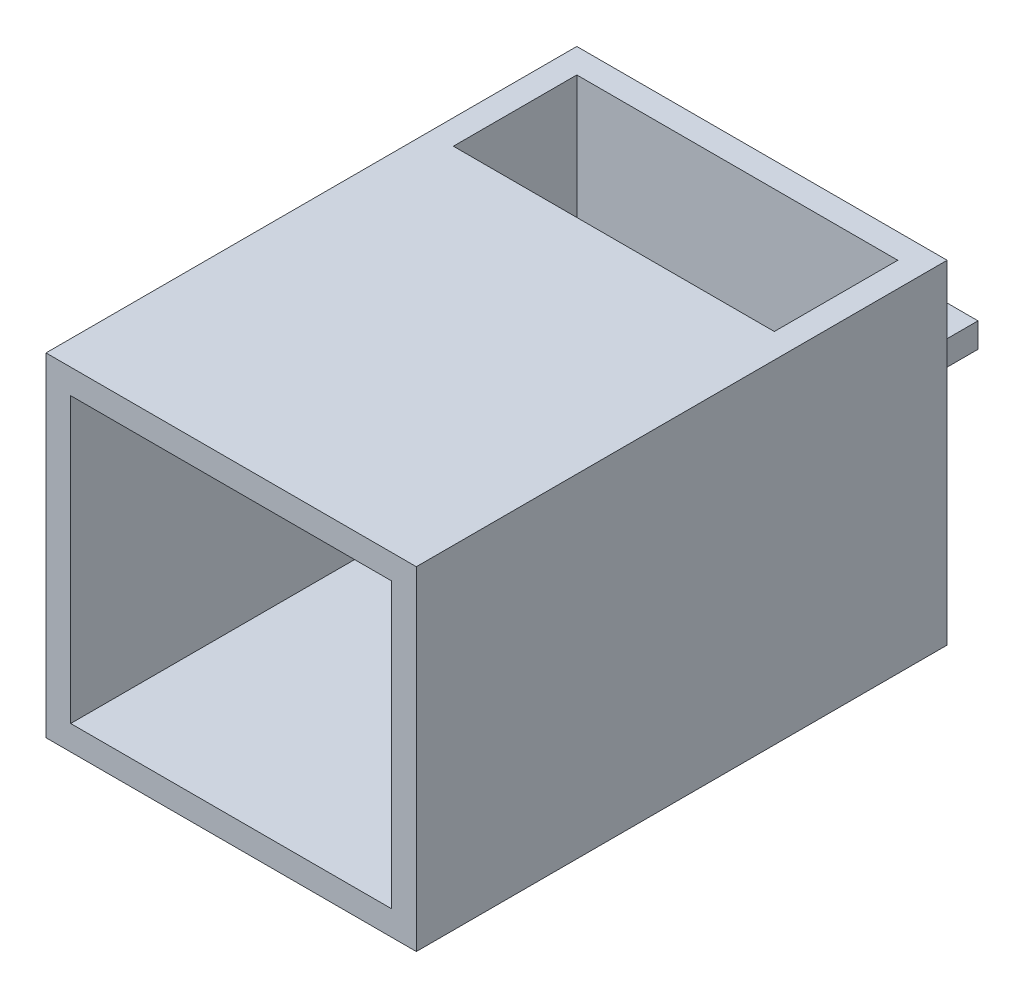
SolidWorks part; units mm, degrees
ref_plane "Front Plane" through (0, 0, 0) normal (0, 0, 1) x (1, 0, 0)
ref_plane "Top Plane" through (0, 0, 0) normal (0, 1, 0) x (1, 0, 0)
ref_plane "Right Plane" through (0, 0, 0) normal (1, 0, 0) x (0, 0, -1)
sketch "Sketch1" plane through (0, 0, 0) normal (0, 0, 1) x (1, 0, 0)
  line L1 (-13, 11.5) -> (13, 11.5)
  line L2 (-13, 11.5) -> (-13, -11.5)
  line L3 (-13, -11.5) -> (13, -11.5)
  line L4 (13, 11.5) -> (13, -11.5)
  line L5 (-13, 11.5) -> (13, -11.5) construction
  line L6 (-13, -11.5) -> (13, 11.5) construction
  line L7 (-15, 13.5) -> (15, 13.5)
  line L8 (-15, 13.5) -> (-15, -13.5)
  line L9 (-15, -13.5) -> (15, -13.5)
  line L10 (15, 13.5) -> (15, -13.5)
  line L11 (-15, 13.5) -> (15, -13.5) construction
  line L12 (-15, -13.5) -> (15, 13.5) construction
  point P0 (0, 0)
  point P6 (0, 0)
  dimension "D1" = 23
  dimension "D2" = 26
  dimension "D3" = 2
  dimension "D4" = 2
extrude "Boss-Extrude1" add sketch "Sketch1" along normal blind 43
sketch "Sketch3" plane through (0, 0, 0) normal (0, 0, -1) x (-1, 0, 0)
  line L0 (15, 13.5) -> (15, -13.5) construction
  line L1 (-15, 13.5) -> (15, 13.5)
  line L2 (-15, 13.5) -> (-15, -1.5)
  line L3 (-15, -1.5) -> (15, -1.5)
  line L4 (15, 13.5) -> (15, -1.5)
  line L5 (13, -11.5) -> (-13, -11.5) construction
  dimension "D1" = 10
extrude "Boss-Extrude2" add sketch "Sketch3" against normal blind 2
sketch "Sketch5" plane through (0, 0, 0) normal (0, 0, -1) x (-1, 0, 0)
  line L0 (-13, -1.5) -> (13, -1.5) construction
  line L1 (-7.5, -1.5) -> (7.5, -1.5)
  line L2 (-7.5, -1.5) -> (-7.5, 0.5)
  line L3 (-7.5, 0.5) -> (7.5, 0.5)
  line L4 (7.5, -1.5) -> (7.5, 0.5)
  line L5 (0, 0) -> (0, -1.5) construction
  line L6 (13, -11.5) -> (-13, -11.5) construction
  line L7 (-2.5, -11.5) -> (2.5, -11.5)
  line L8 (-2.5, -11.5) -> (-2.5, -13.5)
  line L9 (-2.5, -13.5) -> (2.5, -13.5)
  line L10 (2.5, -11.5) -> (2.5, -13.5)
  line L11 (15, -13.5) -> (-15, -13.5) construction
  point P17 (0, -11.5)
  dimension "D1" = 15
  dimension "D2" = 2
  dimension "D3" = 5
extrude "Boss-Extrude3" add sketch "Sketch5" along normal blind 10 contours L2 L1 L4 L3 | L8 L7 L10 L9
sketch "Sketch6" plane through (-2.5, 0, 0) normal (-1, 0, 0) x (0, 0, 1)
  line L0 (-5, -13.5) -> (-3, -15.5)
  line L1 (-10, -13.5) -> (0, -13.5) construction
  line L2 (-3, -15.5) -> (-3, -13.5)
  line L3 (-5, -13.5) -> (-3, -13.5)
  line L4 (0, -11.5) -> (0, -13.5) construction
  dimension "D1" = 2
  dimension "D2" = 3
  dimension "D3" = 2
extrude "Boss-Extrude4" add sketch "Sketch6" against normal blind 5
sketch "Sketch7" plane through (0, 0, -10) normal (0, 0, -1) x (-1, 0, 0)
  line L0 (2.5, -11.5) -> (2.5, -13.5) construction
  line L1 (-2.5, -11.5) -> (2.5, -11.5)
  line L2 (-2.5, -11.5) -> (-2.5, -13.5)
  line L3 (-2.5, -13.5) -> (2.5, -13.5)
  line L4 (2.5, -11.5) -> (2.5, -13.5)
  line L5 (2.5, -11.5) -> (2.5, -13.5) construction
extrude "Cut-Extrude1" cut sketch "Sketch7" against normal blind 5
fillet "Fillet3" radius 0.5 3 edges at (0, -11.5, -5) (0, -13.5, -5) (0, -15.5, -3)
sketch "Sketch8" plane through (0, 13.5, 0) normal (0, 1, 0) x (1, 0, 0)
  line L0 (7.5, 0) -> (-7.5, 0) construction
  line L1 (-13, -2) -> (13, -2)
  line L2 (-13, -2) -> (-13, -12)
  line L3 (-13, -12) -> (13, -12)
  line L4 (13, -2) -> (13, -12)
  line L5 (-15, -43) -> (-15, 0) construction
  line L6 (15, -43) -> (15, 0) construction
  dimension "D1" = 2
  dimension "D2" = 2
  dimension "D3" = 2
  dimension "D4" = 10
extrude "Cut-Extrude2" cut sketch "Sketch8" against normal blind 10
